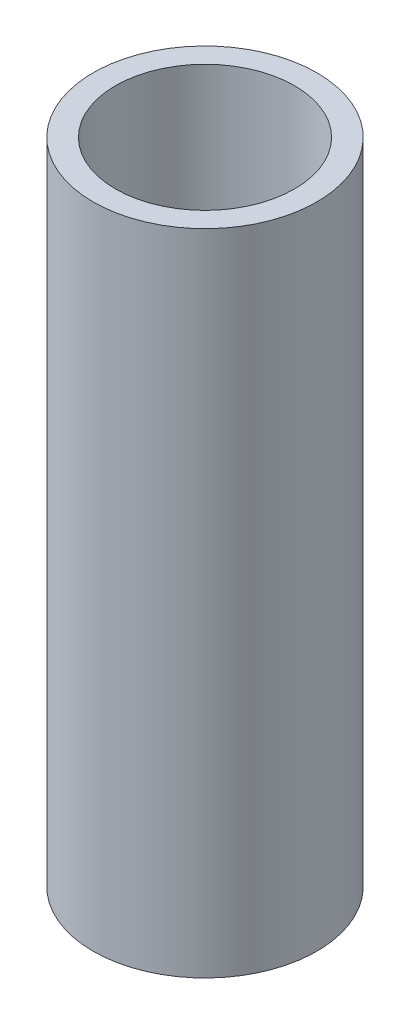
SolidWorks part; units mm, degrees
ref_plane "Front" through (0, 0, 0) normal (0, 0, 1) x (1, 0, 0)
ref_plane "Top" through (0, 0, 0) normal (0, 1, 0) x (1, 0, 0)
ref_plane "Right" through (0, 0, 0) normal (1, 0, 0) x (0, 0, -1)
sketch "Sketch1" plane through (0, 0, 0) normal (0, 1, 0) x (1, 0, 0)
  circle A0 centre (0, 0) radius 4
  circle A1 centre (0, 0) radius 5
  dimension "D2" = 10
  dimension "D1" = 8
extrude "Boss-Extrude1" add sketch "Sketch1" along normal blind 29
